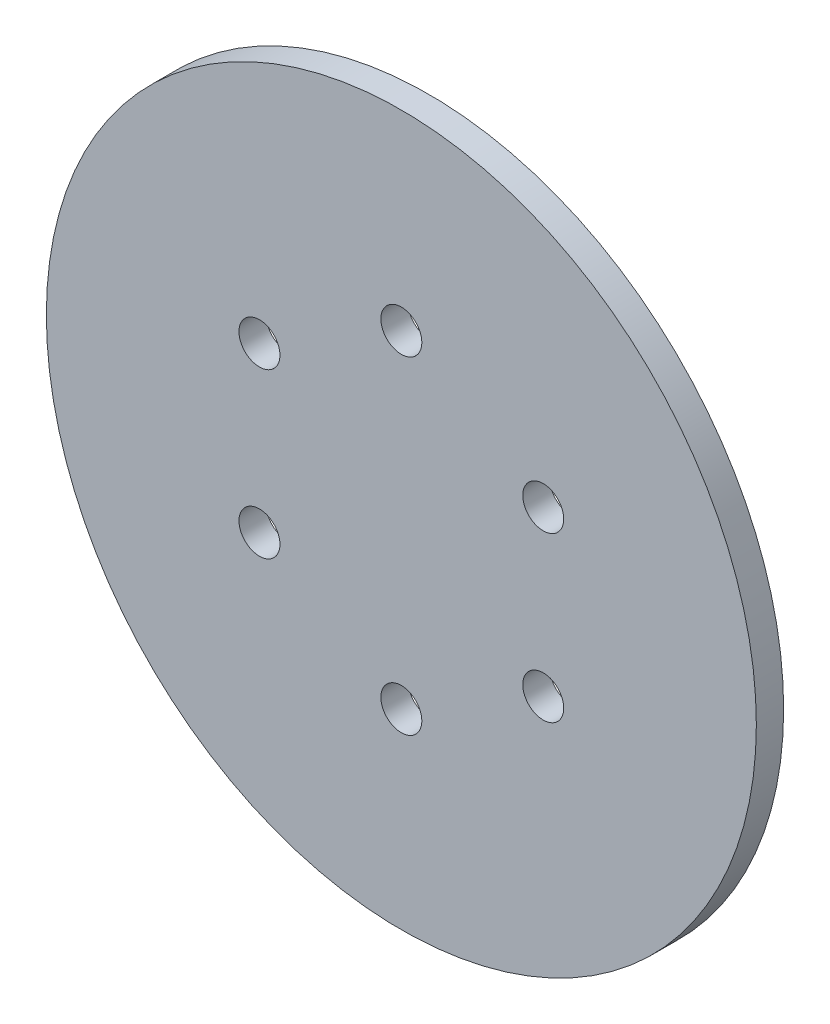
SolidWorks part; units mm, degrees
ref_plane "Front Plane" through (0, 0, 0) normal (0, 0, 1) x (1, 0, 0)
ref_plane "Top Plane" through (0, 0, 0) normal (0, 1, 0) x (1, 0, 0)
ref_plane "Right Plane" through (0, 0, 0) normal (1, 0, 0) x (0, 0, -1)
sketch "Sketch1" plane through (0, 0, 0) normal (0, 0, 1) x (1, 0, 0)
  circle A0 centre (0, 0) radius 41.275
  circle A1 centre (0, 19.05) radius 2.3813
  circle A2 centre (16.4978, 9.525) radius 2.3813
  circle A3 centre (16.4978, -9.525) radius 2.3813
  circle A4 centre (0, -19.05) radius 2.3813
  circle A5 centre (-16.4978, -9.525) radius 2.3813
  circle A6 centre (-16.4978, 9.525) radius 2.3813
  point P18 (0, 0)
  dimension "D1" = 82.55
  dimension "D2" = 4.7625
  dimension "D3" = 19.05
  dimension "D4" = 6
extrude "Boss-Extrude1" add sketch "Sketch1" along normal blind 3.175
